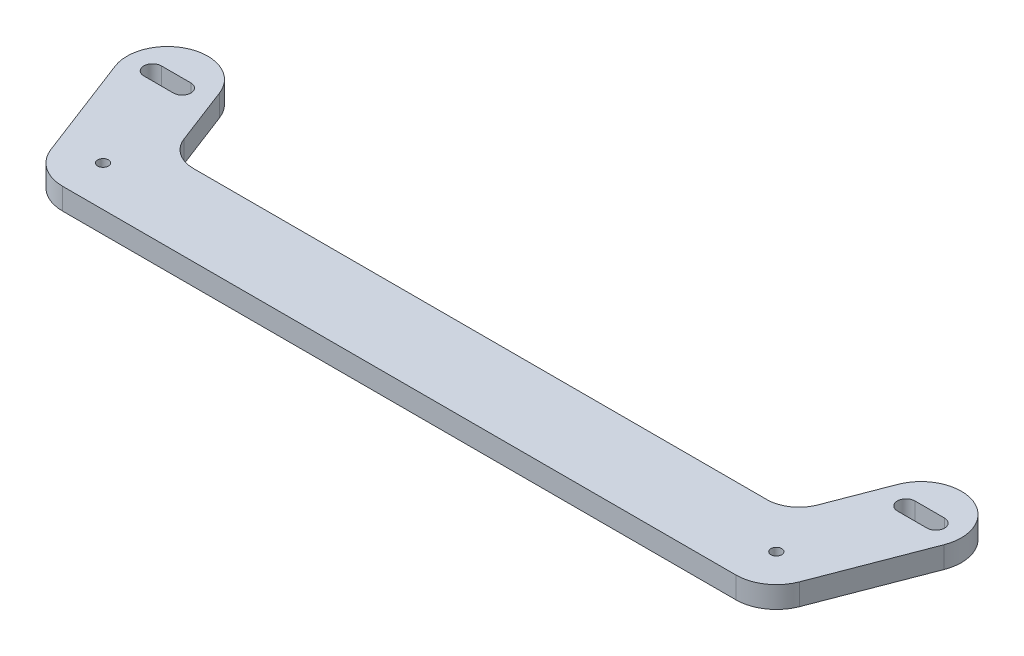
SolidWorks part; units mm, degrees
ref_plane "Front Plane" through (0, 0, 0) normal (0, 0, 1) x (1, 0, 0)
ref_plane "Top Plane" through (0, 0, 0) normal (0, 1, 0) x (1, 0, 0)
ref_plane "Right Plane" through (0, 0, 0) normal (1, 0, 0) x (0, 0, -1)
sketch "Sketch1" plane through (0, 0, 0) normal (0, 1, 0) x (1, 0, 0)
  line L0 (-145.4, 140.4) -> (-134.4, 140.4) construction
  line L1 (-139.9, 140.4) -> (139.9, 140.4) construction
  line L2 (-139.9, 140.4) -> (-139.9, -140.4) construction
  line L3 (-139.9, -140.4) -> (139.9, -140.4) construction
  line L4 (139.9, 140.4) -> (139.9, -140.4) construction
  line L5 (-139.9, 140.4) -> (139.9, -140.4) construction
  line L6 (-139.9, -140.4) -> (139.9, 140.4) construction
  line L7 (-125, 101.6) -> (125, 101.6) construction
  line L8 (-125, 101.6) -> (-125, -101.6) construction
  line L9 (-125, -101.6) -> (125, -101.6) construction
  line L10 (125, 101.6) -> (125, -101.6) construction
  line L11 (-125, 101.6) -> (125, -101.6) construction
  line L12 (-125, -101.6) -> (125, 101.6) construction
  line L13 (-145.4, 143.65) -> (-134.4, 143.65)
  line L14 (-145.4, 137.15) -> (-134.4, 137.15)
  line L15 (145.4, 140.4) -> (134.4, 140.4) construction
  line L16 (145.4, 137.15) -> (134.4, 137.15)
  line L17 (145.4, 143.65) -> (134.4, 143.65)
  line L18 (-145.4, -140.4) -> (-134.4, -140.4) construction
  line L19 (-145.4, -137.15) -> (-134.4, -137.15) construction
  line L20 (-145.4, -143.65) -> (-134.4, -143.65) construction
  line L21 (145.4, -140.4) -> (134.4, -140.4) construction
  line L22 (145.4, -143.65) -> (134.4, -143.65) construction
  line L23 (145.4, -137.15) -> (134.4, -137.15) construction
  line L24 (-130.5, 101.6) -> (-119.5, 101.6) construction
  line L25 (-130.5, 104.35) -> (-119.5, 104.35) construction
  line L26 (-130.5, 98.85) -> (-119.5, 98.85) construction
  line L27 (130.5, 101.6) -> (119.5, 101.6) construction
  line L28 (130.5, 98.85) -> (119.5, 98.85) construction
  line L29 (130.5, 104.35) -> (119.5, 104.35) construction
  line L30 (-130.5, -101.6) -> (-119.5, -101.6) construction
  line L31 (-130.5, -98.85) -> (-119.5, -98.85) construction
  line L32 (-130.5, -104.35) -> (-119.5, -104.35) construction
  line L33 (130.5, -101.6) -> (119.5, -101.6) construction
  line L34 (130.5, -104.35) -> (119.5, -104.35) construction
  line L35 (130.5, -98.85) -> (119.5, -98.85) construction
  line L36 (-125.897, 145.7774) -> (-117.6485, 124.2981)
  line L37 (-106.4461, 116.6) -> (106.4461, 116.6)
  line L39 (139.003, 96.2226) -> (153.903, 135.0226)
  line L40 (125, 86.6) -> (-125, 86.6)
  line L41 (-153.903, 135.0226) -> (-139.003, 96.2226)
  line L42 (117.6485, 124.2981) -> (125.897, 145.7774)
  arc A0 (-145.4, 143.65) -> (-145.4, 137.15) centre (-145.4, 140.4) ccw
  arc A1 (-134.4, 137.15) -> (-134.4, 143.65) centre (-134.4, 140.4) ccw
  arc A2 (145.4, 137.15) -> (145.4, 143.65) centre (145.4, 140.4) ccw
  arc A3 (134.4, 143.65) -> (134.4, 137.15) centre (134.4, 140.4) ccw
  arc A4 (-145.4, -137.15) -> (-145.4, -143.65) centre (-145.4, -140.4) ccw construction
  arc A5 (-134.4, -143.65) -> (-134.4, -137.15) centre (-134.4, -140.4) ccw construction
  arc A6 (145.4, -143.65) -> (145.4, -137.15) centre (145.4, -140.4) ccw construction
  arc A7 (134.4, -137.15) -> (134.4, -143.65) centre (134.4, -140.4) ccw construction
  arc A8 (-130.5, 104.35) -> (-130.5, 98.85) centre (-130.5, 101.6) ccw construction
  arc A9 (-119.5, 98.85) -> (-119.5, 104.35) centre (-119.5, 101.6) ccw construction
  arc A10 (130.5, 98.85) -> (130.5, 104.35) centre (130.5, 101.6) ccw construction
  arc A11 (119.5, 104.35) -> (119.5, 98.85) centre (119.5, 101.6) ccw construction
  arc A12 (-130.5, -98.85) -> (-130.5, -104.35) centre (-130.5, -101.6) ccw construction
  arc A13 (-119.5, -104.35) -> (-119.5, -98.85) centre (-119.5, -101.6) ccw construction
  arc A14 (130.5, -104.35) -> (130.5, -98.85) centre (130.5, -101.6) ccw construction
  arc A15 (119.5, -98.85) -> (119.5, -104.35) centre (119.5, -101.6) ccw construction
  arc A16 (-125.897, 145.7774) -> (-153.903, 135.0226) centre (-139.9, 140.4) ccw
  arc A17 (-139.003, 96.2226) -> (-125, 86.6) centre (-125, 101.6) ccw
  arc A18 (125, 86.6) -> (139.003, 96.2226) centre (125, 101.6) ccw
  arc A19 (153.903, 135.0226) -> (125.897, 145.7774) centre (139.9, 140.4) ccw
  arc A20 (106.4461, 116.6) -> (117.6485, 124.2981) centre (106.4461, 128.6) ccw
  arc A21 (-106.4461, 116.6) -> (-117.6485, 124.2981) centre (-106.4461, 128.6) cw
  circle A22 centre (-125, 101.6) radius 2
  circle A23 centre (125, 101.6) radius 2
  point P0 (0, 0)
  point P6 (0, 0)
  point P13 (-139.9, 140.4)
  point P19 (139.9, 140.4)
  point P26 (-139.9, -140.4)
  point P33 (139.9, -140.4)
  point P41 (-125, 101.6)
  point P47 (125, 101.6)
  point P55 (-125, -101.6)
  point P61 (125, -101.6)
  dimension "D5" = 3.25
  dimension "D7" = 2.75
  dimension "D9" = 30
  dimension "D10" = 12
  dimension "D13" = 4
  dimension "D1" = 279.8
  dimension "D2" = 280.8
  dimension "D3" = 250
  dimension "D4" = 203.2
  dimension "D6" = 11
  dimension "D8" = 11
  dimension "D11" = 30
  dimension "D12" = 30
extrude "Boss-Extrude1" add sketch "Sketch1" along normal blind 8
